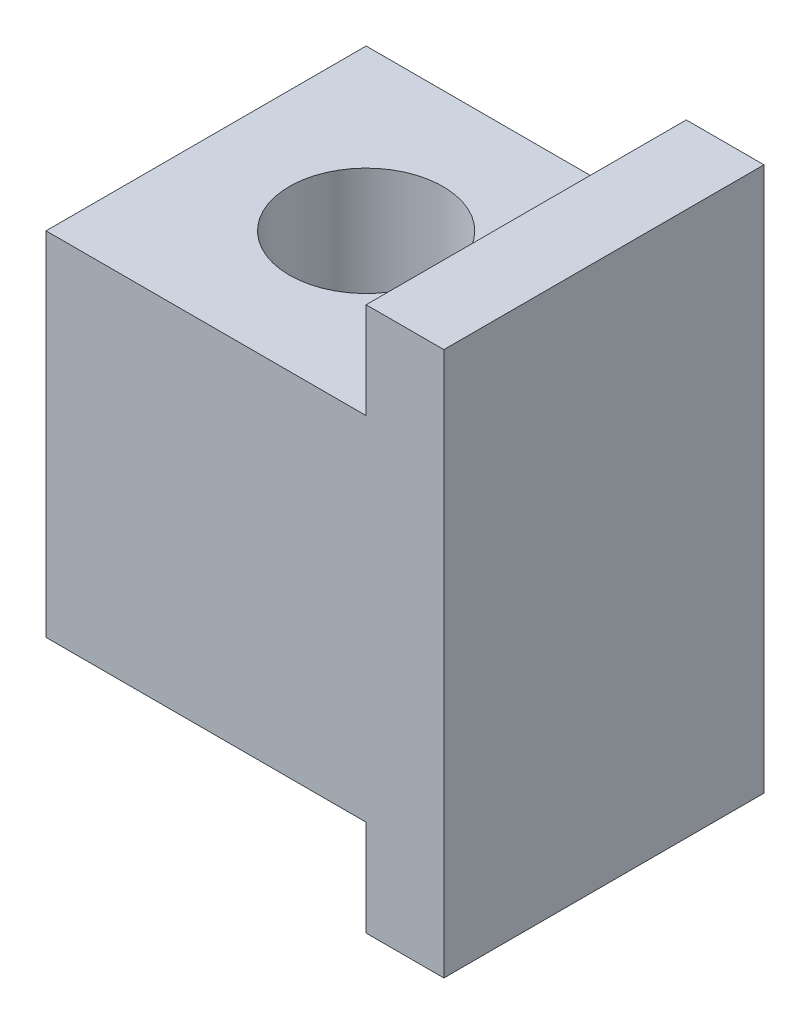
SolidWorks part; units mm, degrees
ref_plane "Front Plane" through (0, 0, 0) normal (0, 0, 1) x (1, 0, 0)
ref_plane "Top Plane" through (0, 0, 0) normal (0, 1, 0) x (1, 0, 0)
ref_plane "Right Plane" through (0, 0, 0) normal (1, 0, 0) x (0, 0, -1)
sketch "Sketch2" plane through (0, 0, 0) normal (0, 0, 1) x (1, 0, 0)
  line L0 (12.7, 0) -> (12.7, 3.81)
  line L1 (0, 0) -> (12.7, 0)
  line L2 (0, 0) -> (0, -13.97)
  line L3 (0, -13.97) -> (12.7, -13.97)
  line L9 (12.7, 3.81) -> (15.7828, 3.81)
  line L10 (15.7828, 3.81) -> (15.7828, -17.78)
  line L11 (15.7828, -17.78) -> (12.7, -17.78)
  line L12 (12.7, -17.78) -> (12.7, -13.97)
  dimension "D1" = 13.97
  dimension "D2" = 12.7
  dimension "D3" = 90
  dimension "D4" = 3.81
  dimension "D5" = 3.81
extrude "Boss-Extrude1" add sketch "Sketch2" along normal blind 12.7
sketch "Sketch3" plane through (0, 0, 0) normal (0, 1, 0) x (1, 0, 0)
  line L0 (0, -12.7) -> (0, 0) construction
  line L1 (12.7, 0) -> (0, 0) construction
  circle A0 centre (6.35, -6.35) radius 3.048
  dimension "D1" = 6.35
  dimension "D2" = 6.35
extrude "Cut-Extrude1" cut sketch "Sketch3" against normal blind 17.78
